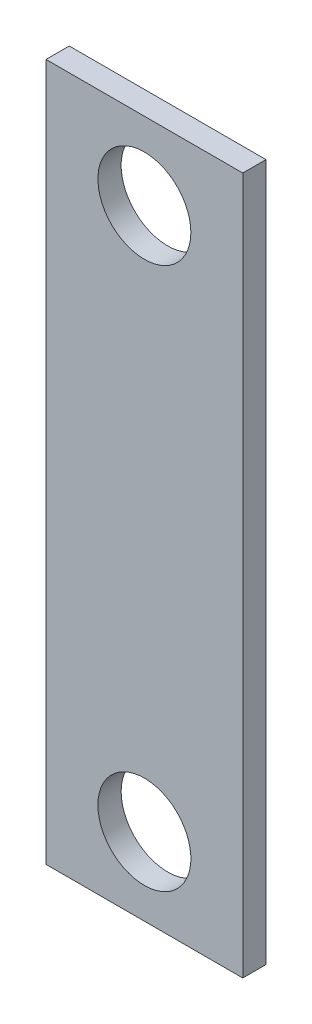
SolidWorks part; units mm, degrees
ref_plane "Alzado" through (0, 0, 0) normal (0, 0, 1) x (1, 0, 0)
ref_plane "Planta" through (0, 0, 0) normal (0, 1, 0) x (1, 0, 0)
ref_plane "Vista lateral" through (0, 0, 0) normal (1, 0, 0) x (0, 0, -1)
sketch "Croquis1" plane through (0, 0, 0) normal (0, 0, 1) x (1, 0, 0)
  line L0 (-43.9789, 0) -> (38.9135, 0) construction
  line L1 (25.4, -90) -> (-25.4, -90)
  line L2 (25.4, -90) -> (25.4, 90)
  line L3 (25.4, 90) -> (-25.4, 90)
  line L4 (-25.4, -90) -> (-25.4, 90)
  line L5 (25.4, -90) -> (-25.4, 90) construction
  line L6 (25.4, 90) -> (-25.4, -90) construction
  circle A0 centre (0, 70) radius 12
  circle A1 centre (0, -70) radius 12
  point P0 (0, 0)
  dimension "D3" = 24
  dimension "D1" = 50.8
  dimension "D2" = 180
  dimension "D4" = 20
extrude "Saliente-Extruir1" add sketch "Croquis1" along normal blind 6
